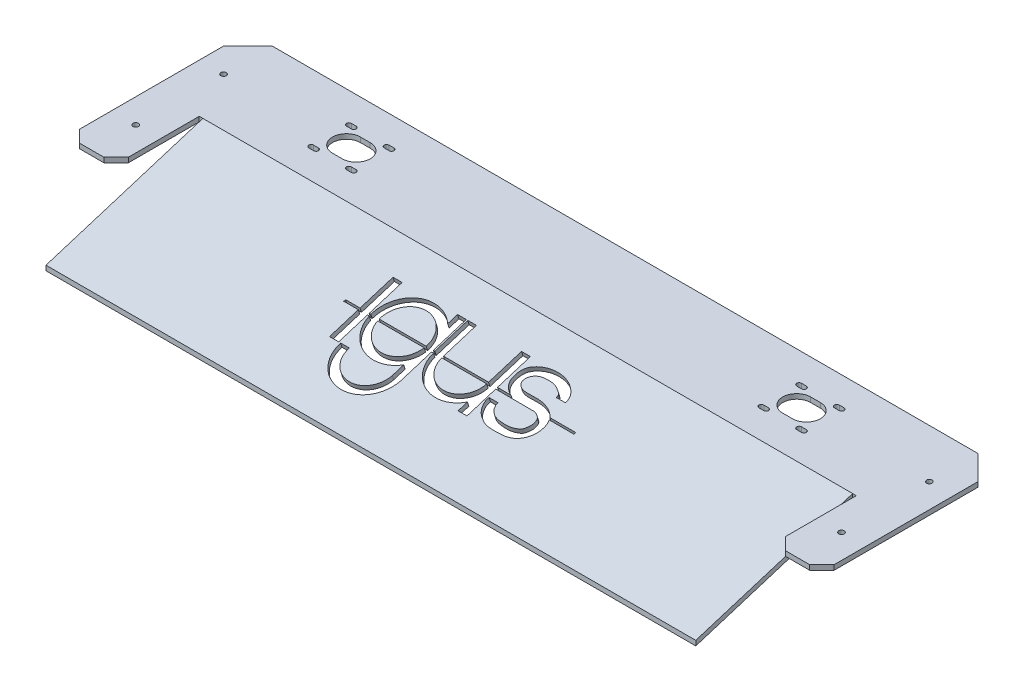
SolidWorks part; units mm, degrees
ref_plane "Front Plane" through (0, 0, 0) normal (0, 0, 1) x (1, 0, 0)
ref_plane "Top Plane" through (0, 0, 0) normal (0, 1, 0) x (1, 0, 0)
ref_plane "Right Plane" through (0, 0, 0) normal (1, 0, 0) x (0, 0, -1)
sketch "Sketch1" plane through (0, 0, 0) normal (0, 1, 0) x (1, 0, 0)
  line L0 (0, 0) -> (-310, 0) construction
  line L1 (-310, 0) -> (-310, 108.2843)
  line L2 (-310, 108.2843) -> (-270, 108.2843)
  line L3 (-270, 108.2843) -> (-270, 68.2843)
  line L4 (-270, 68.2843) -> (-241.7157, 40)
  line L5 (-241.7157, 40) -> (0, 40)
  line L6 (0, 40) -> (0, 0)
  line L7 (-310, 0) -> (0, 0)
  line L8 (-189, 0) -> (-181, 0) construction
  line L9 (-189, 11.5) -> (-181, 11.5)
  line L10 (-202.4998, 15.4998) -> (-198.4998, 15.4998) construction
  line L11 (-185, 0) -> (-220.6507, 35.6507) construction
  line L12 (-202.4998, 17.4998) -> (-198.4998, 17.4998)
  line L13 (-202.4998, 13.4998) -> (-198.4998, 13.4998)
  line L14 (-185, 11.5) -> (-185, 25.0205) construction
  line L15 (-167.5002, 15.4998) -> (-171.5002, 15.4998) construction
  line L16 (-167.5002, 17.4998) -> (-171.5002, 17.4998)
  line L17 (-167.5002, 13.4998) -> (-171.5002, 13.4998)
  arc A0 (-189, 11.5) -> (-200.5, 0) centre (-189, 0) ccw
  arc A1 (-169.5, 0) -> (-181, 11.5) centre (-181, 0) ccw
  arc A2 (-202.4998, 17.4998) -> (-202.4998, 13.4998) centre (-202.4998, 15.4998) ccw
  arc A3 (-198.4998, 13.4998) -> (-198.4998, 17.4998) centre (-198.4998, 15.4998) ccw
  arc A4 (-167.5002, 17.4998) -> (-167.5002, 13.4998) centre (-167.5002, 15.4998) cw
  arc A5 (-171.5002, 13.4998) -> (-171.5002, 17.4998) centre (-171.5002, 15.4998) cw
  point P10 (-185, 0)
  point P19 (-200.4998, 15.4998)
  point P28 (-169.5002, 15.4998)
  dimension "D9" = 11.5
  dimension "D11" = 2
  dimension "D1" = 310
  dimension "D2" = 40
  dimension "D3" = 40
  dimension "D4" = 40
  dimension "D5" = 40
  dimension "D6" = 135
  dimension "D7" = 185
  dimension "D8" = 4
  dimension "D10" = 21.92
  dimension "D12" = 4
extrude "Boss-Extrude1" add sketch "Sketch1" along normal blind 4 contours A1 L7 L6 L5 L4 L3 L2 L1 A0 L9
mirror "Mirror1" about plane through (0, 4, 0) normal (0, 0, -1) of "Boss-Extrude1"
mirror "Mirror5" about plane through (0, 4, 0) normal (1, 0, 0) of "Boss-Extrude1"
mirror "Mirror6" about plane through (0, 4, 0) normal (0, 0, 1) of "Mirror5"
sketch "Sketch2" plane through (0, 4, 0) normal (0, 1, 0) x (1, 0, 0)
  line L0 (-290, -36.0948) -> (-290, -72.1895)
  line L2 (-290, 36.0948) -> (-290, 0) construction
  line L3 (-290, 0) -> (-290, -36.0948) construction
  line L4 (-290, -72.1895) -> (-290, -108.2843)
  line L6 (-310, -108.2843) -> (-270, -108.2843) construction
  line L7 (-290, 36.0948) -> (-290, 72.1895)
  line L8 (-290, 72.1895) -> (-290, 108.2843)
  line L9 (-310, 108.2843) -> (-270, 108.2843) construction
  circle A0 centre (-290, 72.1895) radius 2.25
  circle A1 centre (-290, -72.1895) radius 2.25
  circle A2 centre (-290, 0) radius 2.25
  dimension "D1" = 4.5
extrude "Cut-Extrude1" cut sketch "Sketch2" against normal blind 44 contours L4 A1 L0 | L0 A1 L4 | A2 | L7 A0 L8 | L8 A0 L7
chamfer "Chamfer1" distance 10 angle 45 4 edges at (-270, 2, 108.2843) (-310, 2, 108.2843) (-310, 2, -108.2843) (-270, 2, -108.2843)
mirror "Mirror9" about plane through (0, 0, 0) normal (1, 0, 0) of "Cut-Extrude1"
chamfer "Chamfer2" distance 10 angle 45 4 edges at (310, 2, 108.2843) (270, 2, 108.2843) (270, 2, -108.2843) (310, 2, -108.2843)
sketch "Sketch3" plane through (0, 4, 0) normal (0, 1, 0) x (1, 0, 0)
  line L0 (-82.0648, 19.0507) -> (317.9352, 19.0507) construction
  line L1 (-21.8464, -9.8238) -> (-17.085, -9.8238)
  line L2 (-27.9324, 26.5851) -> (-22.9462, 26.5851)
  line L3 (-27.9324, 26.5851) -> (-27.9324, 7.69)
  line L4 (-27.9324, -9.8238) -> (-22.9462, -9.8238)
  line L5 (-22.9462, 26.5851) -> (-22.9462, 7.69)
  line L6 (7.4256, 20.9291) -> (7.4256, 26.5851)
  line L8 (48.1768, 1.992) -> (53.0651, 1.992)
  line L9 (12.1869, -10.8785) -> (12.1869, 26.5851)
  line L10 (12.1869, 26.5851) -> (7.4256, 26.5851)
  line L11 (7.4256, -10.8785) -> (7.4256, -4.32)
  line L12 (42.4602, 7.69) -> (42.4602, 26.5851)
  line L13 (42.4602, -9.8238) -> (47.3516, -9.8238)
  line L14 (42.4602, -9.8238) -> (42.4602, -4.4171)
  line L15 (42.4602, 26.5851) -> (47.3516, 26.5851)
  line L16 (47.3516, -9.8238) -> (47.3516, 6.6736)
  line L17 (70.9024, 16.7119) -> (75.9269, 16.7119)
  line L18 (17.7563, 26.5851) -> (13.034, 26.5851)
  line L19 (17.7563, 26.5851) -> (17.7563, 7.69)
  line L20 (17.7563, 7.69) -> (42.4602, 7.69)
  line L21 (13.034, 26.5851) -> (13.034, 7.69)
  line L22 (-27.9324, 6.6736) -> (-27.9324, -9.8238)
  line L23 (-35.9318, 7.69) -> (-27.9324, 7.69)
  line L24 (-35.9318, 7.69) -> (-35.9318, 6.6736)
  line L25 (-35.9318, 6.6736) -> (-27.9324, 6.6736)
  line L26 (82.484, 7.69) -> (82.484, 6.6736)
  line L27 (-22.9462, 7.69) -> (-22.0144, 7.69)
  line L28 (-22.9462, 6.6736) -> (-21.9488, 6.6736)
  line L29 (-22.9462, 6.6736) -> (-22.9462, -9.8238)
  line L30 (-17.4632, 7.69) -> (8.2752, 7.69)
  line L31 (-17.3742, 6.6736) -> (8.1862, 6.6736)
  line L32 (12.1869, 7.69) -> (13.034, 7.69)
  line L33 (12.1869, 6.6736) -> (13.2257, 6.6736)
  line L34 (17.7569, 6.6736) -> (42.4532, 6.6736)
  line L35 (76.0197, 7.69) -> (82.484, 7.69)
  line L36 (76.6898, 6.6736) -> (82.484, 6.6736)
  line L37 (47.3516, 7.69) -> (47.3516, 26.5851)
  line L38 (69.0253, 6.5779) -> (47.3516, 6.6736)
  line L39 (54.7056, 7.69) -> (47.3516, 7.69)
  circle A0 centre (-25.5805, 32.4181) radius 2.3986
  arc A1 (-17.3742, 6.6736) -> (8.1862, 6.6736) centre (-4.594, 8.3045) ccw
  arc A2 (7.4256, 20.9291) -> (-22.0144, 7.69) centre (-4.594, 8.3045) ccw
  arc A3 (-17.085, -9.8238) -> (7.4256, -10.8785) centre (-4.8297, -10.3511) ccw
  arc A4 (12.1869, -10.8785) -> (-21.8464, -9.8238) centre (-4.8297, -10.3511) cw
  arc A5 (17.7569, 6.6736) -> (42.4532, 6.6736) centre (30.105, 7.091) ccw
  arc A6 (13.2257, 6.6736) -> (42.4602, -4.4171) centre (30.105, 7.091) ccw
  arc A7 (-21.9488, 6.6736) -> (7.4256, -4.32) centre (-4.594, 8.3045) ccw
  arc A8 (8.2752, 7.69) -> (-17.4632, 7.69) centre (-4.594, 8.3045) ccw
  spline S0 degree 3 poles (75.9269, 16.7119) (76.1697, 20.3324) (70.9484, 25.553) (61.7695, 27.1891) (54.3456, 25.3692) (49.1183, 21.0552) (48.6509, 16.3068) (49.3938, 11.1111) (52.398, 8.5199) (54.7056, 7.69) knots 0 0 0 0 0.214336 0.39323 0.565847 0.67611 0.787927 0.84268 1 1 1 1
  spline S1 degree 3 poles (70.9024, 16.7119) (71.1665, 17.5271) (70.3325, 18.7995) (68.5625, 19.9226) (66.2905, 21.192) (63.4484, 21.6366) (60.1841, 21.5266) (57.2636, 21.0924) (54.8065, 19.4136) (53.435, 17.2465) (53.3745, 14.8515) (54.797, 13.1138) (58.5993, 11.576) (64.2118, 12.5728) (70.2856, 11.558) (74.0797, 9.743) (75.5817, 8.254) (76.0197, 7.69) knots 0 0 0 0 0.023974 0.0429 0.065707 0.104505 0.130316 0.168034 0.194386 0.220522 0.245719 0.2628 0.28726 0.369622 0.434467 0.476788 0.498808 0.498808 0.498808 0.498808
  spline S2 degree 3 poles (53.0651, 1.992) (52.8818, 1.0624) (53.4653, -0.024) (54.1041, -1.4919) (54.9804, -2.2675) (55.9906, -3.2538) (57.4527, -4.0034) (59.3948, -4.5243) (61.6145, -4.7083) (64.1331, -4.7695) (66.6176, -4.5389) (68.8285, -3.7825) (70.9655, -2.8167) (71.9855, -0.7891) (72.7896, 1.157) (72.6963, 3.0645) (72.0298, 5.4733) (69.9357, 6.0483) (69.0253, 6.5779) knots 0 0 0 0 0.081184 0.107905 0.143901 0.185104 0.235866 0.290216 0.366526 0.436729 0.518739 0.590002 0.64943 0.723575 0.786666 0.838093 0.894822 1 1 1 1
  spline S3 degree 3 poles (76.6898, 6.6736) (76.7767, 6.5153) (77.3461, 5.3791) (77.8424, 2.7751) (77.4957, -0.9697) (75.8419, -4.3239) (73.3769, -6.9875) (70.4757, -8.5808) (67.3839, -9.2832) (63.9164, -9.4499) (60.2497, -9.5065) (56.621, -9.1479) (53.7606, -7.5828) (51.0815, -5.941) (48.8083, -2.5373) (47.9106, 0.1666) (48.1768, 1.992) knots 0.51138 0.51138 0.51138 0.51138 0.516991 0.550898 0.592187 0.632311 0.665074 0.704087 0.733344 0.763284 0.81203 0.848329 0.874619 0.912981 0.944693 1 1 1 1
sketch "Sketch4" plane through (0, 4, 0) normal (0, 1, 0) x (1, 0, 0)
  line L0 (0, -40) -> (0, 40) construction
  line L1 (-241.7157, -40) -> (241.7157, -40) construction
  line L2 (-241.7157, 40) -> (241.7157, 40) construction
extrude "Cut-Extrude2" cut sketch "Sketch3" against normal blind 10 contours L0 L21 L32 L9 L33 A6 L14 L13 L16 L38 S2 L8 S3 L36 L26 L35 S1 S0 L39 L37 L12 L20 L19 A5 L34 | L0 L3 L23 L24 L25 L22 L4 L29 L28 A7 L11 A3 L1 A4 L9 A8 L30 A2 L27 L5 A1 L31 | L0 S1 L17 S0 | S0 L0 S1 | L12 L0 L37 L15 | L21 L0 L19 L18 | A2 L0 A8 L9 L10 L6 | L3 L0 L5 L2 | A0
sketch "Sketch5" plane through (0, 4, 0) normal (0, 1, 0) x (1, 0, 0)
  line L0 (-270, -68.2843) -> (-241.7157, -40)
  line L1 (-241.7157, -40) -> (-270, -40)
  line L2 (-270, -40) -> (-270, -68.2843)
  line L3 (241.7157, -40) -> (270, -68.2843)
  line L4 (270, -68.2843) -> (270, -40)
  line L5 (270, -40) -> (241.7157, -40)
extrude "Cut-Extrude3" cut sketch "Sketch5" against normal blind 10
sketch "Sketch6" plane through (0, 0, 0) normal (1, 0, 0) x (0, 0, -1)
  line L0 (-40, 4) -> (-168.938, -36)
  line L1 (-168.938, -36) -> (-168.938, -40)
  line L2 (-168.938, -40) -> (-40, 0)
  line L3 (-40, 0) -> (-40, 4)
  dimension "D1" = 135
  dimension "D2" = 40
extrude "Boss-Extrude2" add sketch "Sketch6" along normal mid plane 534
sketch "Sketch7" plane through (0, 14.9685, 4.6436) normal (0, 0.9551, 0.2963) x (1, 0, 0)
  line L0 (-74.9706, -119.5218) -> (-67.8286, -119.5218)
  line L1 (-84.0997, -64.9084) -> (-76.6204, -64.9084)
  line L2 (-84.0997, -64.9084) -> (-84.0997, -93.251)
  line L3 (-84.0997, -119.5218) -> (-76.6204, -119.5218)
  line L4 (-76.6204, -64.9084) -> (-76.6204, -93.251)
  line L5 (-31.0627, -73.3925) -> (-31.0627, -64.9084)
  line L6 (30.0641, -101.7981) -> (37.3966, -101.7981)
  line L7 (-23.9207, -121.1039) -> (-23.9207, -64.9084)
  line L8 (-23.9207, -64.9084) -> (-31.0627, -64.9084)
  line L9 (-31.0627, -121.1039) -> (-31.0627, -111.2661)
  line L10 (21.4893, -93.251) -> (21.4893, -64.9084)
  line L11 (21.4893, -119.5218) -> (28.8263, -119.5218)
  line L12 (21.4893, -119.5218) -> (21.4893, -111.4117)
  line L13 (21.4893, -64.9084) -> (28.8263, -64.9084)
  line L14 (28.8263, -119.5218) -> (28.8263, -94.7757)
  line L15 (64.1525, -79.7183) -> (71.6893, -79.7183)
  line L16 (-15.5666, -64.9084) -> (-22.65, -64.9084)
  line L17 (-15.5666, -64.9084) -> (-15.5666, -93.251)
  line L18 (-15.5666, -93.251) -> (21.4893, -93.251)
  line L19 (-22.65, -64.9084) -> (-22.65, -93.251)
  line L20 (-84.0997, -94.7757) -> (-84.0997, -119.5218)
  line L21 (-96.0988, -93.251) -> (-84.0997, -93.251)
  line L22 (-96.0988, -93.251) -> (-96.0988, -94.7757)
  line L23 (-96.0988, -94.7757) -> (-84.0997, -94.7757)
  line L24 (93.1423, -93.251) -> (93.1423, -94.7757)
  line L25 (-76.6204, -93.251) -> (-75.2227, -93.251)
  line L26 (-76.6204, -94.7757) -> (-75.1243, -94.7757)
  line L27 (-76.6204, -94.7757) -> (-76.6204, -119.5218)
  line L28 (-68.3958, -93.251) -> (-29.7883, -93.251)
  line L29 (-68.2624, -94.7757) -> (-29.9218, -94.7757)
  line L30 (-23.9207, -93.251) -> (-22.65, -93.251)
  line L31 (-23.9207, -94.7757) -> (-22.3625, -94.7757)
  line L32 (-15.5657, -94.7757) -> (21.4787, -94.7757)
  line L33 (71.8285, -93.251) -> (93.1423, -93.251)
  line L34 (72.8337, -94.7757) -> (93.1423, -94.7757)
  line L35 (28.8263, -93.251) -> (28.8263, -64.9084)
  line L36 (61.3369, -94.9193) -> (28.8263, -94.7757)
  line L37 (39.8573, -93.251) -> (28.8263, -93.251)
  line L38 (-96.0988, -94.7757) -> (-371.9782, -94.7757) construction
  line L40 (93.1423, -94.7757) -> (369.0218, -94.7757) construction
  circle A0 centre (-80.5717, -56.159) radius 3.5979
  arc A1 (-68.2624, -94.7757) -> (-29.9218, -94.7757) centre (-49.0921, -92.3293) ccw
  arc A2 (-31.0627, -73.3925) -> (-75.2227, -93.251) centre (-49.0921, -92.3293) ccw
  arc A3 (-67.8286, -119.5218) -> (-31.0627, -121.1039) centre (-49.4456, -120.3128) ccw
  arc A4 (-23.9207, -121.1039) -> (-74.9706, -119.5218) centre (-49.4456, -120.3128) cw
  arc A5 (-15.5657, -94.7757) -> (21.4787, -94.7757) centre (2.9565, -94.1497) ccw
  arc A6 (-22.3625, -94.7757) -> (21.4893, -111.4117) centre (2.9565, -94.1497) ccw
  arc A7 (-75.1243, -94.7757) -> (-31.0627, -111.2661) centre (-49.0921, -92.3293) ccw
  arc A8 (-29.7883, -93.251) -> (-68.3958, -93.251) centre (-49.0921, -92.3293) ccw
  spline S0 degree 3 poles (71.6893, -79.7183) (72.0536, -74.2875) (64.2215, -66.4567) (50.4532, -64.0025) (39.3174, -66.7324) (31.4763, -73.2033) (30.7753, -80.3259) (31.8896, -88.1195) (36.3959, -92.0062) (39.8573, -93.251) knots 0 0 0 0 0.214336 0.39323 0.565847 0.67611 0.787927 0.84268 1 1 1 1
  spline S1 degree 3 poles (64.1525, -79.7183) (64.5486, -78.4955) (63.2977, -76.5869) (60.6427, -74.9022) (57.2347, -72.9982) (52.9716, -72.3312) (48.075, -72.4963) (43.6944, -73.1475) (40.0087, -75.6657) (37.9514, -78.9163) (37.8607, -82.5089) (39.9945, -85.1154) (45.6979, -87.4221) (54.1166, -85.9268) (63.2273, -87.4491) (68.9185, -90.1717) (71.1716, -92.4052) (71.8285, -93.251) knots 0 0 0 0 0.023974 0.0429 0.065707 0.104505 0.130316 0.168034 0.194386 0.220522 0.245719 0.2628 0.28726 0.369622 0.434467 0.476788 0.498808 0.498808 0.498808 0.498808
  spline S2 degree 3 poles (37.3966, -101.7981) (37.1217, -103.1924) (37.9969, -104.8221) (38.9551, -107.0239) (40.2695, -108.1873) (41.7848, -109.6668) (43.978, -110.7913) (46.8911, -111.5726) (50.2207, -111.8486) (53.9986, -111.9403) (57.7254, -111.5945) (61.0418, -110.4599) (64.2473, -109.0111) (65.7772, -105.9697) (66.9834, -103.0506) (66.8435, -100.1894) (65.8437, -96.5761) (62.7025, -95.7137) (61.3369, -94.9193) knots 0 0 0 0 0.081184 0.107905 0.143901 0.185104 0.235866 0.290216 0.366526 0.436729 0.518739 0.590002 0.64943 0.723575 0.786666 0.838093 0.894822 1 1 1 1
  spline S3 degree 3 poles (72.8337, -94.7757) (72.964, -95.0131) (73.8181, -96.7175) (74.5625, -100.6235) (74.0425, -106.2407) (71.5619, -111.272) (67.8644, -115.2673) (63.5125, -117.6573) (58.8748, -118.7109) (53.6736, -118.961) (48.1735, -119.0459) (42.7305, -118.508) (38.4399, -116.1603) (34.4212, -113.6977) (31.0114, -108.592) (29.6648, -104.5362) (30.0641, -101.7981) knots 0.51138 0.51138 0.51138 0.51138 0.516991 0.550898 0.592187 0.632311 0.665074 0.704087 0.733344 0.763284 0.81203 0.848329 0.874619 0.912981 0.944693 1 1 1 1
extrude "Cut-Extrude4" cut sketch "Sketch7" against normal blind 494 contours L26 A7 L9 A3 L0 A4 L7 L8 L5 A2 L25 L4 L1 L2 L21 L22 L23 L20 L3 L27 A8 L28 A1 L29 | S3 L34 L24 L33 S1 L15 S0 L37 L35 L13 L10 L18 L17 L16 L19 L30 L7 L31 A6 L12 L11 L14 L36 S2 L6 A5 L32
sketch "Sketch8" plane through (0, 4, 0) normal (0, 1, 0) x (1, 0, 0)
  line L0 (-241.7157, 40) -> (241.7157, 40) construction
  line L1 (-117.7008, 40) -> (117.1851, 40)
  line L2 (-117.7008, 40) -> (-117.7008, -40)
  line L3 (-117.7008, -40) -> (117.1851, -40)
  line L4 (117.1851, 40) -> (117.1851, -40)
  line L5 (267, -40) -> (-267, -40) construction
extrude "Boss-Extrude3" add sketch "Sketch8" against normal up to surface (4 mm away) up to face at (-25.5805, 0, -30.0195)
sketch "Sketch9" plane through (0, 4, 0) normal (0, 1, 0) x (1, 0, 0)
  line L0 (241.7157, 40) -> (-241.7157, 40) construction
  line L1 (399.3947, 40) -> (-391.8377, 40)
  line L2 (399.3947, 40) -> (399.3947, 234.8199)
  line L3 (399.3947, 234.8199) -> (-391.8377, 234.8199)
  line L4 (-391.8377, 40) -> (-391.8377, 234.8199)
extrude "Cut-Extrude5" cut sketch "Sketch9" against normal blind 139
chamfer "Chamfer3" distance 20 angle 45 2 edges at (310, 2, -40) (-310, 2, -40)
